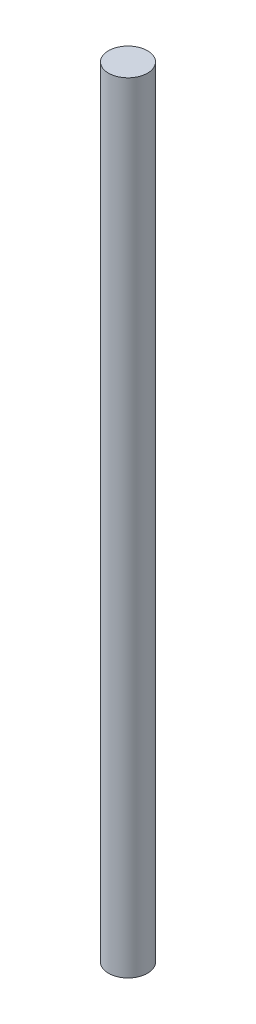
SolidWorks part; units mm, degrees
ref_plane "Front Plane" through (0, 0, 0) normal (0, 0, 1) x (1, 0, 0)
ref_plane "Top Plane" through (0, 0, 0) normal (0, 1, 0) x (1, 0, 0)
ref_plane "Right Plane" through (0, 0, 0) normal (1, 0, 0) x (0, 0, -1)
sketch "草圖1" plane through (0, 0, 0) normal (0, 1, 0) x (1, 0, 0)
  circle A0 centre (0, 0) radius 1.75
  dimension "D1" = 3.5
extrude "填料-伸長1" add sketch "草圖1" along normal blind 70
